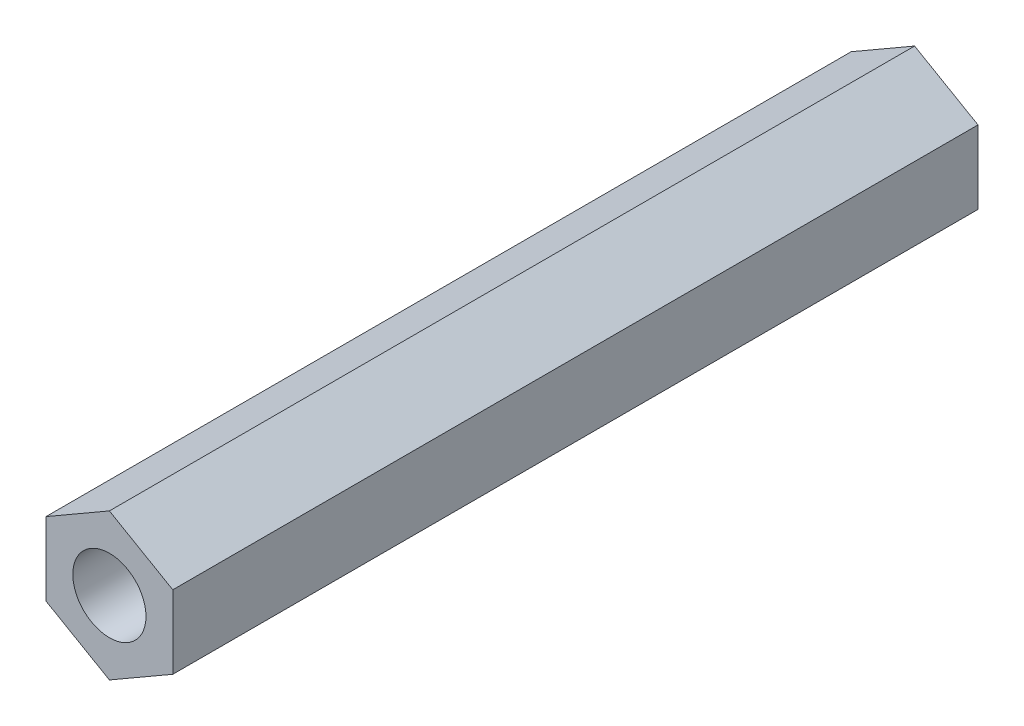
SolidWorks part; units mm, degrees
ref_plane "Front Plane" through (0, 0, 0) normal (0, 0, 1) x (1, 0, 0)
ref_plane "Top Plane" through (0, 0, 0) normal (0, 1, 0) x (1, 0, 0)
ref_plane "Right Plane" through (0, 0, 0) normal (1, 0, 0) x (0, 0, -1)
sketch "Sketch1" plane through (0, 0, 0) normal (0, 0, 1) x (1, 0, 0)
  line L1 (0, 0.5) -> (-0.433, 0.25)
  line L2 (-0.433, 0.25) -> (-0.433, -0.25)
  line L3 (-0.433, -0.25) -> (0, -0.5)
  line L4 (0, -0.5) -> (0.433, -0.25)
  line L5 (0.433, -0.25) -> (0.433, 0.25)
  line L6 (0.433, 0.25) -> (0, 0.5)
  circle A0 centre (0, 0) radius 0.433 construction
  dimension "D1" = 1
extrude "Boss-Extrude1" add sketch "Sketch1" along normal blind 5.5
sketch "Sketch2" plane through (0, 0, 5.5) normal (0, 0, 1) x (1, 0, 0)
  circle A0 centre (0, 0) radius 0.25
  dimension "D1" = 0.5
extrude "Cut-Extrude1" cut sketch "Sketch2" against normal blind 5.5
